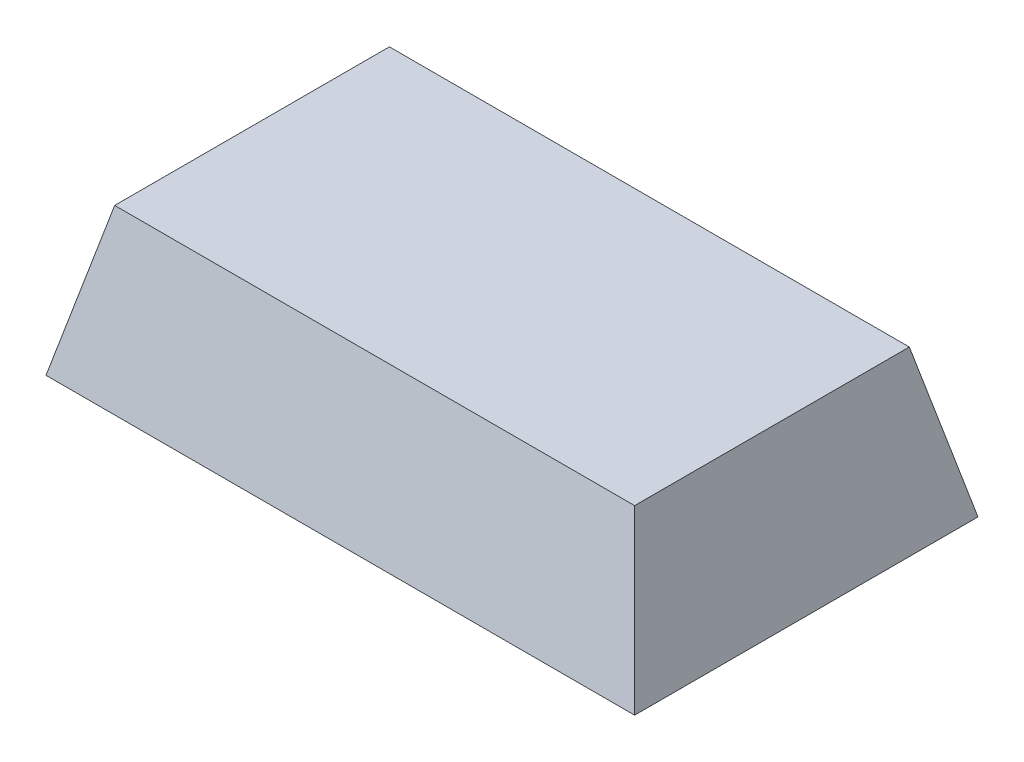
SolidWorks part; units mm, degrees
ref_plane "Front Plane" through (0, 0, 0) normal (0, 0, 1) x (1, 0, 0)
ref_plane "Top Plane" through (0, 0, 0) normal (0, 1, 0) x (1, 0, 0)
ref_plane "Right Plane" through (0, 0, 0) normal (1, 0, 0) x (0, 0, -1)
sketch "Sketch1" plane through (0, 0, 0) normal (0, 1, 0) x (1, 0, 0)
  line L1 (0, 0) -> (12, 0)
  line L2 (0, 0) -> (0, 7)
  line L3 (0, 7) -> (12, 7)
  line L4 (12, 0) -> (12, 7)
  dimension "D1" = 7
  dimension "D2" = 12
extrude "Boss-Extrude1" add sketch "Sketch1" along normal blind 3
sketch "Sketch2" plane through (0, 0, 0) normal (0, 0, 1) x (1, 0, 0)
  line L0 (0, 0) -> (0.7, 3)
  line L1 (0, 3) -> (12, 3) construction
  line L2 (0.7, 3) -> (0, 3)
  line L3 (0, 3) -> (0, 0)
  line L4 (12, 0) -> (11.3, 3)
  line L5 (11.3, 3) -> (12, 3)
  line L6 (12, 3) -> (12, 0)
  dimension "D1" = 0.7
  dimension "D2" = 0.7
extrude "Cut-Extrude1" cut sketch "Sketch2" against normal blind 7
sketch "Sketch3" plane through (0, 0, 0) normal (1, 0, 0) x (0, 0, -1)
  line L0 (0, 0) -> (0.7, 3)
  line L1 (7, 3) -> (0, 3) construction
  line L2 (0.7, 3) -> (0, 3)
  line L3 (0, 3) -> (0, 0)
  line L4 (7, 3) -> (6.3, 3)
  line L5 (6.3, 3) -> (7, 0)
  line L6 (7, 3) -> (7, 0)
  dimension "D1" = 0.7
  dimension "D2" = 0.7
extrude "Cut-Extrude2" cut sketch "Sketch3" along normal through all both and the other way through all
sketch "Sketch4" plane through (0, 0, 0) normal (0, -1, 0) x (1, 0, 0)
  line L0 (6, 0) -> (6, -7) construction
  line L1 (0, 0) -> (12, 0) construction
  line L2 (12, -7) -> (0, -7) construction
  line L3 (0, -3.5) -> (12, -3.5) construction
  line L4 (0, -7) -> (0, 0) construction
  line L5 (12, 0) -> (12, -7) construction
  circle A0 centre (6, -3.5) radius 1.8
  dimension "D1" = 3.6
extrude "Cut-Extrude3" cut sketch "Sketch4" against normal blind 0.8
